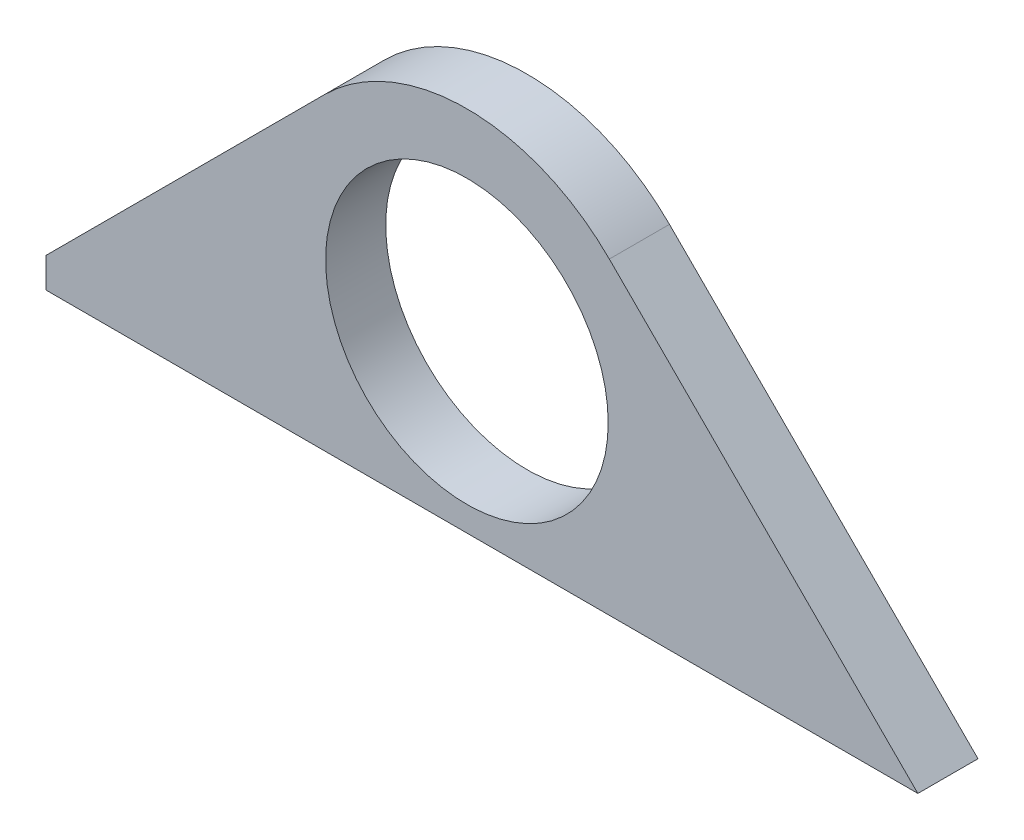
SolidWorks part; units mm, degrees
ref_plane "Plan de face" through (0, 0, 0) normal (0, 0, 1) x (1, 0, 0)
ref_plane "Plan de dessus" through (0, 0, 0) normal (0, 1, 0) x (1, 0, 0)
ref_plane "Plan de droite" through (0, 0, 0) normal (1, 0, 0) x (0, 0, -1)
sketch "Esquisse1" plane through (0, 0, 0) normal (0, 0, 1) x (1, 0, 0)
  line L0 (0, 0) -> (140, 0)
  line L1 (140, 0) -> (140, 5) construction
  line L2 (140, 5) -> (100, 45) construction
  line L3 (100, 45) -> (23.094, 45) construction
  line L4 (23.094, 45) -> (0, 5) construction
  line L5 (0, 5) -> (0, 0)
  line L6 (0, 5) -> (140, 5) construction
  line L7 (61.547, 45) -> (61.547, 5) construction
  line L8 (140, 5) -> (70, 75) construction
  line L9 (0, 5) -> (70, 75) construction
  line L10 (140, 5) -> (93.6881, 51.3119)
  line L11 (46.3119, 51.3119) -> (0, 5)
  line L12 (140, 0) -> (145, 0)
  line L13 (145, 0) -> (140, 5)
  arc A0 (46.3119, 51.3119) -> (93.6881, 51.3119) centre (70, 27.6238) cw
  circle A1 centre (70, 27.6238) radius 23.5
  dimension "D6" = 10
  dimension "D8" = 47
  dimension "D5" = 40
  dimension "D1" = 5
  dimension "D2" = 140
  dimension "D3" = 60
  dimension "D4" = 45
extrude "Boss.-Extru.1" add sketch "Esquisse1" along normal blind 10
